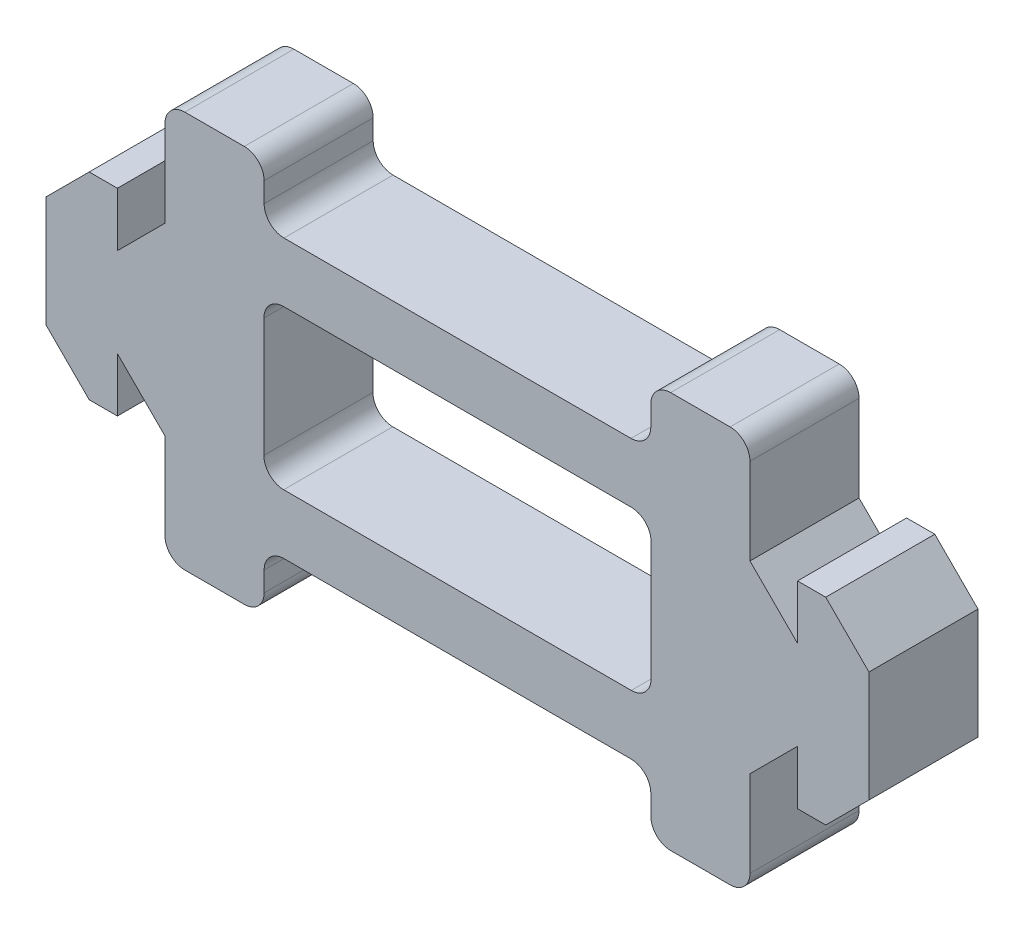
SolidWorks part; units mm, degrees
ref_plane "Front Plane" through (0, 0, 0) normal (0, 0, 1) x (1, 0, 0)
ref_plane "Top Plane" through (0, 0, 0) normal (0, 1, 0) x (1, 0, 0)
ref_plane "Right Plane" through (0, 0, 0) normal (1, 0, 0) x (0, 0, -1)
sketch "Sketch1" plane through (0, 0, 0) normal (0, 0, 1) x (1, 0, 0)
  line L0 (15.6876, 55.3211) -> (115.0437, 55.3211) construction
  line L1 (8.1, 5.225) -> (8.1, 2.85)
  line L2 (-8.5, 10) -> (-4.75, 10)
  line L3 (-10, 8.5) -> (-10, 4.75)
  line L4 (-8.5, -10) -> (-4.75, -10)
  line L5 (10, 8.5) -> (10, 4.75)
  line L6 (6.325, 5.225) -> (4, 2.9)
  line L7 (-8.1, -2.85) -> (-8.1, -5.225)
  line L8 (-2.9, 4) -> (2.9, 4)
  line L9 (-4, 2.9) -> (-4, -2.9)
  line L10 (-2.9, -4) -> (2.9, -4)
  line L11 (4, 2.9) -> (4, -2.9)
  line L12 (2.85, -8.1) -> (5.225, -8.1)
  line L13 (-5.225, -8.1) -> (-2.85, -8.1)
  line L14 (5.225, 6.325) -> (2.9, 4)
  line L15 (-6.4286, 4.975) -> (-4.25, 2.7964)
  line L16 (-4.25, 2.7964) -> (-4.25, -2.7964)
  line L17 (-10, 4.75) -> (-8.1, 2.85)
  line L18 (-4.25, -2.7964) -> (-6.4286, -4.975)
  line L19 (-7.85, -4.975) -> (-6.4286, -4.975)
  line L20 (4.75, -10) -> (8.5, -10)
  line L21 (-7.85, -2.2464) -> (-7.85, -4.975)
  line L22 (-10, -4.75) -> (-10, -8.5)
  line L23 (10, -4.75) -> (10, -8.5)
  line L24 (-10, -4.75) -> (-8.1, -2.85)
  line L25 (-4.75, -10) -> (-2.85, -8.1)
  line L26 (4.75, -10) -> (2.85, -8.1)
  line L27 (10, -4.75) -> (8.1, -2.85)
  line L28 (10, 4.75) -> (8.1, 2.85)
  line L29 (-4.75, 10) -> (-2.85, 8.1)
  line L30 (4.75, 10) -> (2.85, 8.1)
  line L31 (8.1, -2.85) -> (8.1, -5.225)
  line L32 (6.325, -5.225) -> (8.1, -5.225)
  line L33 (5.225, -6.325) -> (5.225, -8.1)
  line L34 (4.75, 10) -> (8.5, 10)
  line L35 (2.85, 8.1) -> (5.225, 8.1)
  line L36 (10, -10) -> (10.975, -10.975) construction
  line L37 (-5.225, 8.1) -> (-2.85, 8.1)
  line L38 (-8.1, -5.225) -> (-6.325, -5.225)
  line L39 (-5.225, 6.325) -> (-2.9, 4)
  line L40 (-8.1, 5.225) -> (-8.1, 2.85)
  line L41 (-5.225, -6.325) -> (-5.225, -8.1)
  line L42 (-6.325, 5.225) -> (-4, 2.9)
  line L43 (-10.25, -4.6464) -> (-7.85, -2.2464)
  line L44 (-10.25, -4.6464) -> (-10.25, -8.5)
  line L45 (-8.5, -10.25) -> (-4.6464, -10.25)
  line L46 (-8.1, 5.225) -> (-6.325, 5.225)
  line L47 (-5.225, 8.1) -> (-5.225, 6.325)
  line L48 (-4.6464, -10.25) -> (-2.2464, -7.85)
  line L49 (-4.975, -7.85) -> (-2.2464, -7.85)
  line L50 (-4.975, -6.4286) -> (-4.975, -7.85)
  line L51 (-2.7964, -4.25) -> (-4.975, -6.4286)
  line L52 (8.1, 5.225) -> (6.325, 5.225)
  line L53 (5.225, 8.1) -> (5.225, 6.325)
  line L54 (-2.7964, -4.25) -> (2.7964, -4.25)
  line L55 (2.7964, -4.25) -> (4.975, -6.4286)
  line L56 (4.975, -6.4286) -> (4.975, -7.85)
  line L57 (2.2464, -7.85) -> (4.975, -7.85)
  line L58 (4.6464, -10.25) -> (2.2464, -7.85)
  line L59 (4.6464, -10.25) -> (8.5, -10.25)
  line L60 (10.25, -4.6464) -> (10.25, -8.5)
  line L61 (10.25, -4.6464) -> (7.85, -2.2464)
  line L62 (7.85, -2.2464) -> (7.85, -4.975)
  line L63 (4, -2.9) -> (6.325, -5.225)
  line L64 (6.4286, -4.975) -> (7.85, -4.975)
  line L65 (4.25, -2.7964) -> (6.4286, -4.975)
  line L66 (2.9, -4) -> (5.225, -6.325)
  line L67 (-2.9, -4) -> (-5.225, -6.325)
  line L68 (4.25, 2.7964) -> (4.25, -2.7964)
  line L69 (6.4286, 4.975) -> (4.25, 2.7964)
  line L70 (-4, -2.9) -> (-6.325, -5.225)
  line L71 (7.85, 4.975) -> (6.4286, 4.975)
  line L72 (7.85, 4.975) -> (7.85, 2.2464)
  line L73 (10.25, 4.6464) -> (7.85, 2.2464)
  line L74 (10.25, 8.5) -> (10.25, 4.6464)
  line L75 (4.6464, 10.25) -> (8.5, 10.25)
  line L76 (4.6464, 10.25) -> (2.2464, 7.85)
  line L77 (2.2464, 7.85) -> (4.975, 7.85)
  line L78 (4.975, 7.85) -> (4.975, 6.4286)
  line L79 (4.975, 6.4286) -> (2.7964, 4.25)
  line L80 (-2.7964, 4.25) -> (2.7964, 4.25)
  line L81 (-4.975, 6.4286) -> (-2.7964, 4.25)
  line L82 (-4.975, 7.85) -> (-4.975, 6.4286)
  line L83 (-4.975, 7.85) -> (-2.2464, 7.85)
  line L84 (-4.6464, 10.25) -> (-2.2464, 7.85)
  line L85 (-8.5, 10.25) -> (-4.6464, 10.25)
  line L86 (-10.25, 8.5) -> (-10.25, 4.6464)
  line L87 (-10.25, 4.6464) -> (-7.85, 2.2464)
  line L88 (-7.85, 4.975) -> (-7.85, 2.2464)
  line L89 (-7.85, 4.975) -> (-6.4286, 4.975)
  line L90 (0, 0) -> (74.0125, 0.5542) construction
  line L91 (25, 17.7695) -> (25, -17.7695) construction
  line L92 (40, -10) -> (39.025, -10.975) construction
  line L93 (57.85, 4.975) -> (56.4286, 4.975)
  line L94 (57.85, 4.975) -> (57.85, 2.2464)
  line L95 (60.25, 4.6464) -> (57.85, 2.2464)
  line L96 (60.25, 8.5) -> (60.25, 4.6464)
  line L97 (54.6464, 10.25) -> (52.2464, 7.85)
  line L98 (54.975, 7.85) -> (52.2464, 7.85)
  line L99 (54.975, 7.85) -> (54.975, 6.4286)
  line L100 (54.975, 6.4286) -> (52.7964, 4.25)
  line L101 (52.7964, 4.25) -> (47.2036, 4.25)
  line L102 (45.025, 6.4286) -> (47.2036, 4.25)
  line L103 (45.025, 7.85) -> (45.025, 6.4286)
  line L104 (47.7536, 7.85) -> (45.025, 7.85)
  line L105 (45.3536, 10.25) -> (47.7536, 7.85)
  line L106 (45.3536, 10.25) -> (41.5, 10.25)
  line L107 (39.75, 8.5) -> (39.75, 4.6464)
  line L108 (39.75, 4.6464) -> (42.15, 2.2464)
  line L109 (42.15, 4.975) -> (42.15, 2.2464)
  line L110 (42.15, 4.975) -> (43.5714, 4.975)
  line L111 (54, -2.9) -> (56.325, -5.225)
  line L112 (43.5714, 4.975) -> (45.75, 2.7964)
  line L113 (45.75, 2.7964) -> (45.75, -2.7964)
  line L114 (52.9, -4) -> (55.225, -6.325)
  line L115 (47.1, -4) -> (44.775, -6.325)
  line L116 (45.75, -2.7964) -> (43.5714, -4.975)
  line L117 (43.5714, -4.975) -> (42.15, -4.975)
  line L118 (46, -2.9) -> (43.675, -5.225)
  line L119 (42.15, -2.2464) -> (42.15, -4.975)
  line L120 (39.75, -4.6464) -> (42.15, -2.2464)
  line L121 (39.75, -4.6464) -> (39.75, -8.5)
  line L122 (45.3536, -10.25) -> (41.5, -10.25)
  line L123 (45.3536, -10.25) -> (47.7536, -7.85)
  line L124 (47.7536, -7.85) -> (45.025, -7.85)
  line L125 (45.025, -6.4286) -> (45.025, -7.85)
  line L126 (47.2036, -4.25) -> (45.025, -6.4286)
  line L127 (52.7964, -4.25) -> (47.2036, -4.25)
  line L128 (44.775, 8.1) -> (44.775, 6.325)
  line L129 (41.9, 5.225) -> (43.675, 5.225)
  line L130 (52.7964, -4.25) -> (54.975, -6.4286)
  line L131 (54.975, -6.4286) -> (54.975, -7.85)
  line L132 (54.975, -7.85) -> (52.2464, -7.85)
  line L133 (54.6464, -10.25) -> (52.2464, -7.85)
  line L134 (55.225, 8.1) -> (55.225, 6.325)
  line L135 (58.1, 5.225) -> (56.325, 5.225)
  line L136 (58.5, -10.25) -> (54.6464, -10.25)
  line L137 (60.25, -4.6464) -> (60.25, -8.5)
  line L138 (60.25, -4.6464) -> (57.85, -2.2464)
  line L139 (56.325, 5.225) -> (54, 2.9)
  line L140 (55.225, -6.325) -> (55.225, -8.1)
  line L141 (58.1, 5.225) -> (58.1, 2.85)
  line L142 (55.225, 6.325) -> (52.9, 4)
  line L143 (58.1, -5.225) -> (56.325, -5.225)
  line L144 (55.225, 8.1) -> (52.85, 8.1)
  line L145 (47.15, 8.1) -> (44.775, 8.1)
  line L146 (45.25, 10) -> (41.5, 10)
  line L147 (44.775, -6.325) -> (44.775, -8.1)
  line L148 (43.675, -5.225) -> (41.9, -5.225)
  line L149 (41.9, -2.85) -> (41.9, -5.225)
  line L150 (45.25, 10) -> (47.15, 8.1)
  line L151 (54.75, 10) -> (52.85, 8.1)
  line L152 (40, 4.75) -> (41.9, 2.85)
  line L153 (40, -4.75) -> (41.9, -2.85)
  line L154 (45.25, -10) -> (47.15, -8.1)
  line L155 (54.75, -10) -> (52.85, -8.1)
  line L156 (60, -4.75) -> (58.1, -2.85)
  line L157 (40, -4.75) -> (40, -8.5)
  line L158 (60, -4.75) -> (60, -8.5)
  line L159 (57.85, -2.2464) -> (57.85, -4.975)
  line L160 (45.25, -10) -> (41.5, -10)
  line L161 (57.85, -4.975) -> (56.4286, -4.975)
  line L162 (54.25, -2.7964) -> (56.4286, -4.975)
  line L163 (60, 4.75) -> (58.1, 2.85)
  line L164 (54.25, 2.7964) -> (54.25, -2.7964)
  line L165 (56.4286, 4.975) -> (54.25, 2.7964)
  line L166 (44.775, 6.325) -> (47.1, 4)
  line L167 (55.225, -8.1) -> (52.85, -8.1)
  line L168 (47.15, -8.1) -> (44.775, -8.1)
  line L169 (46, 2.9) -> (46, -2.9)
  line L170 (52.9, -4) -> (47.1, -4)
  line L171 (54, 2.9) -> (54, -2.9)
  line L172 (52.9, 4) -> (47.1, 4)
  line L173 (58.1, -2.85) -> (58.1, -5.225)
  line L174 (43.675, 5.225) -> (46, 2.9)
  line L175 (40, 8.5) -> (40, 4.75)
  line L176 (58.5, -10) -> (54.75, -10)
  line L177 (60, 8.5) -> (60, 4.75)
  line L178 (58.5, 10) -> (54.75, 10)
  line L179 (41.9, 5.225) -> (41.9, 2.85)
  line L180 (58.5, 10.25) -> (54.6464, 10.25)
  line L181 (39.75, -8.5) -> (39.75, -10)
  line L182 (-12.75, -10) -> (62.75, -10)
  line L183 (-12.75, -10) -> (-12.75, 10)
  line L184 (-12.75, 10) -> (62.75, 10)
  line L185 (62.75, -10) -> (62.75, 10)
  line L186 (-12.75, -10) -> (62.75, 10) construction
  line L187 (-12.75, 10) -> (62.75, -10) construction
  line L188 (39.75, 8.5) -> (39.75, 10)
  line L189 (10.25, 8.5) -> (10.25, 10)
  line L190 (10.25, -8.5) -> (10.25, -10)
  arc A0 (-8.5, -10) -> (-10, -8.5) centre (-8.5, -8.5) cw
  arc A1 (8.5, -10) -> (10, -8.5) centre (8.5, -8.5) ccw
  arc A2 (10, 8.5) -> (8.5, 10) centre (8.5, 8.5) ccw
  arc A3 (-8.5, 10) -> (-10, 8.5) centre (-8.5, 8.5) ccw
  circle A4 centre (0, 0) radius 2.125
  arc A5 (-8.5, -10.25) -> (-10.25, -8.5) centre (-8.5, -8.5) cw
  arc A6 (8.5, -10.25) -> (10.25, -8.5) centre (8.5, -8.5) ccw
  arc A7 (10.25, 8.5) -> (8.5, 10.25) centre (8.5, 8.5) ccw
  arc A8 (-8.5, 10.25) -> (-10.25, 8.5) centre (-8.5, 8.5) ccw
  arc A9 (58.5, 10.25) -> (60.25, 8.5) centre (58.5, 8.5) cw
  arc A10 (39.75, 8.5) -> (41.5, 10.25) centre (41.5, 8.5) cw
  arc A11 (41.5, -10.25) -> (39.75, -8.5) centre (41.5, -8.5) cw
  arc A12 (58.5, -10.25) -> (60.25, -8.5) centre (58.5, -8.5) ccw
  circle A13 centre (50, 0) radius 2.125
  arc A14 (58.5, 10) -> (60, 8.5) centre (58.5, 8.5) cw
  arc A15 (40, 8.5) -> (41.5, 10) centre (41.5, 8.5) cw
  arc A16 (41.5, -10) -> (40, -8.5) centre (41.5, -8.5) cw
  arc A17 (58.5, -10) -> (60, -8.5) centre (58.5, -8.5) ccw
  point P2 (0, 0)
  point P8 (0, 0)
  point P14 (-10, -10)
  point P20 (0, 0)
  point P49 (10, 10)
  point P52 (-10, 10)
  point P120 (-10, -6.625)
  point P124 (25, 0)
  point P189 (60, 10)
  point P214 (40, 10)
  point P231 (60, -10)
  dimension "D3" = 1.5
  dimension "D4" = 4.25
  dimension "D1" = 20
  dimension "D2" = 20
  dimension "D5" = 0.25
  dimension "D6" = 70
  dimension "D7" = 0.25
  dimension "D8" = 75.5
  dimension "D9" = 20
  dimension "D13" = 5.25
  dimension "D14" = 5.25
  dimension "D15" = 90
  dimension "D16" = 5.25
  dimension "D17" = 5.25
  dimension "D18" = 5.25
  dimension "D19" = 5.25
  dimension "D20" = 5.25
  dimension "D21" = 5.25
  dimension "D22" = 90
  dimension "D23" = 90
  dimension "D24" = 90
  dimension "D25" = 2.85
  dimension "D26" = 2.85
  dimension "D27" = 2.85
  dimension "D28" = 2.85
extrude "Boss-Extrude1" add sketch "Sketch1" along normal blind 5.5 contours L60 L190 L182 L181 L121 L120 L119 L117 L116 L113 L112 L110 L109 L108 L107 L188 L184 L189 L74 L73 L72 L71 L69 L68 L65 L64 L62 L61
sketch "Sketch3" plane through (0, 0, 5.5) normal (0, 0, 1) x (1, 0, 0)
  line L0 (25, 10) -> (25, -10) construction
  line L1 (10.25, 10) -> (39.75, 10) construction
  line L2 (10.25, -10) -> (39.75, -10) construction
  line L3 (10.25, 4.6464) -> (10.25, 10) construction
  line L4 (34.75, 7) -> (15.25, 7)
  line L5 (34.75, 7) -> (34.75, 10)
  line L6 (34.75, 10) -> (15.25, 10)
  line L7 (15.25, 7) -> (15.25, 10)
  line L8 (34.75, 7) -> (15.25, 10) construction
  line L9 (34.75, 10) -> (15.25, 7) construction
  line L11 (34.75, -7) -> (15.25, -7)
  line L12 (34.75, -7) -> (34.75, -10)
  line L13 (34.75, -10) -> (15.25, -10)
  line L14 (15.25, -7) -> (15.25, -10)
  line L15 (34.75, -7) -> (15.25, -10) construction
  line L16 (34.75, -10) -> (15.25, -7) construction
  line L17 (34.7639, -4) -> (15.2361, -4)
  line L18 (34.7639, -4) -> (34.7639, 4)
  line L19 (34.7639, 4) -> (15.2361, 4)
  line L20 (15.2361, -4) -> (15.2361, 4)
  line L21 (34.7639, -4) -> (15.2361, 4) construction
  line L22 (34.7639, 4) -> (15.2361, -4) construction
  point P6 (25, 8.5)
  point P13 (25, -8.5)
  point P18 (25, 0)
  dimension "D1" = 3
  dimension "D2" = 5
  dimension "D3" = 3
  dimension "D4" = 3
extrude "Cut-Extrude1" cut sketch "Sketch3" against normal through all
fillet "Fillet1" radius 1 16 edges at (15.2361, 4, 2.75) (34.7639, 4, 2.75) (34.7639, -4, 2.75) (15.2361, -4, 2.75) (15.25, 7, 2.75) (34.75, 7, 2.75) (34.75, 10, 2.75) (39.75, 10, 2.75) (39.75, -10, 2.75) (34.75, -10, 2.75) (34.75, -7, 2.75) (15.25, -7, 2.75) (15.25, -10, 2.75) (10.25, -10, 2.75) (10.25, 10, 2.75) (15.25, 10, 2.75)
